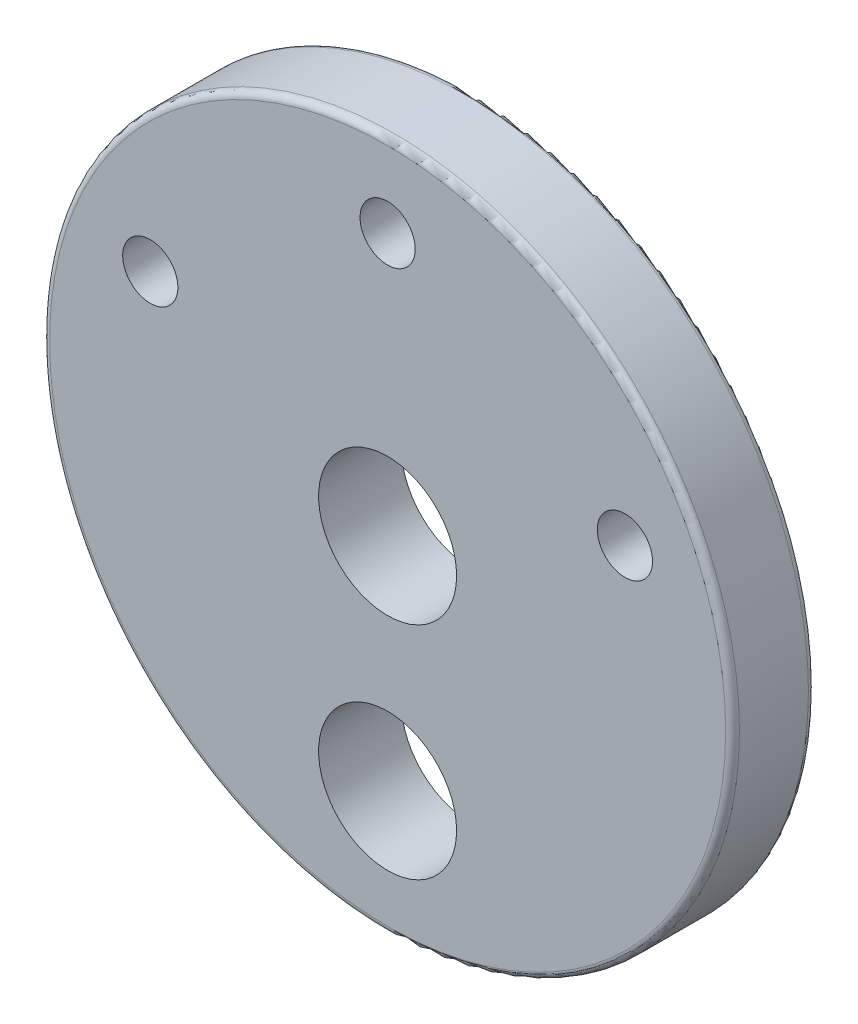
SolidWorks part; units mm, degrees
material "Copper"
ref_plane "Front Plane" through (0, 0, 0) normal (0, 0, 1) x (1, 0, 0)
ref_plane "Top Plane" through (0, 0, 0) normal (0, 1, 0) x (1, 0, 0)
ref_plane "Right Plane" through (0, 0, 0) normal (1, 0, 0) x (0, 0, -1)
sketch "Sketch1" plane through (0, 0, 0) normal (0, 0, 1) x (1, 0, 0)
  circle A0 centre (0, 0) radius 12.5
  dimension "D1" = 25
extrude "Boss-Extrude1" add sketch "Sketch1" along normal blind 3
sketch "Sketch2" plane through (0, 0, 3) normal (0, 0, 1) x (1, 0, 0)
  circle A0 centre (0, 0) radius 2.5
  circle A1 centre (0, -8) radius 2.5
  circle A3 centre (0, 9.5) radius 1
  circle A4 centre (8.6, 4) radius 1
  circle A5 centre (-8.6, 4) radius 1
  dimension "D1" = 5
  dimension "D3" = 5
  dimension "D4" = 2
  dimension "D2" = 8
  dimension "D5" = 8.6
  dimension "D6" = 8.6
  dimension "D7" = 9.5
  dimension "D8" = 4
extrude "Cut-Extrude1" cut sketch "Sketch2" against normal blind 3
cosmetic thread "Cosmetic Thread1" parameters "D2"=15
fillet "Fillet1" radius 0.25 2 edges at (12.5, 0, 0) (12.5, 0, 3)
